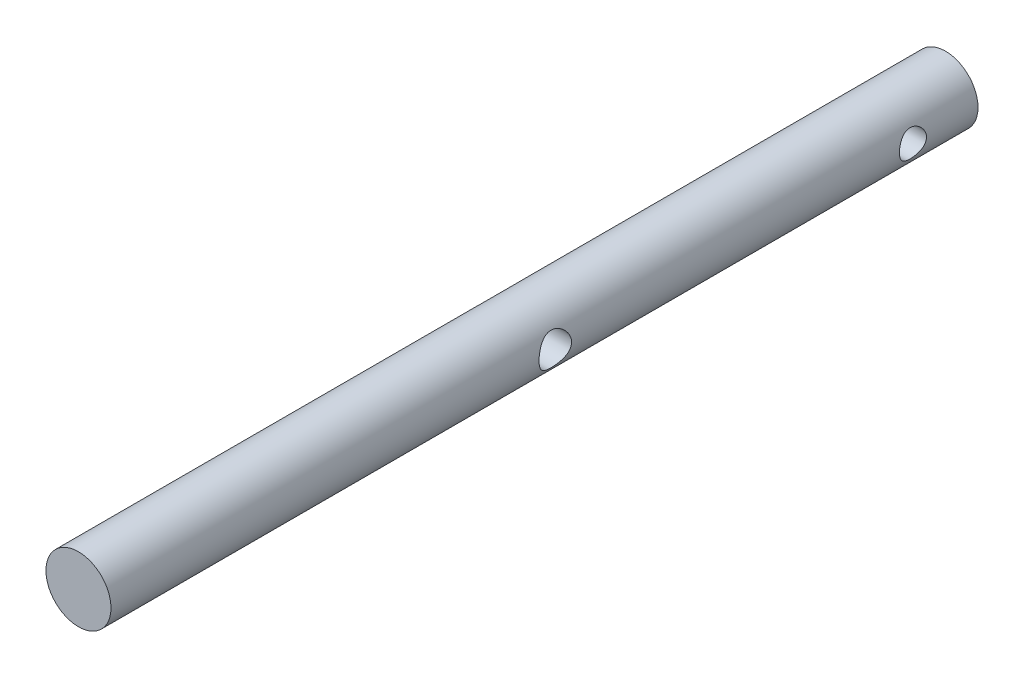
SolidWorks part; units mm, degrees
ref_plane "Front" through (0, 0, 0) normal (0, 0, 1) x (1, 0, 0)
ref_plane "Top" through (0, 0, 0) normal (0, 1, 0) x (1, 0, 0)
ref_plane "Right" through (0, 0, 0) normal (1, 0, 0) x (0, 0, -1)
sketch "Esquisse1" plane through (0, 0, 0) normal (0, 0, 1) x (1, 0, 0)
  circle A0 centre (0, 0) radius 2 construction
  circle A1 centre (0, 0) radius 3
  dimension "D1" = 6
  dimension "D2" = 4
extrude "Boss.-Extru.1" add sketch "Esquisse1" along normal blind 80
sketch "Esquisse2" plane through (0, 0, 0) normal (1, 0, 0) x (0, 0, -1)
  line L0 (0, -3) -> (0, 3) construction
  circle A0 centre (-6, 0) radius 1.25
  circle A1 centre (-39, 0) radius 1.5
  dimension "D1" = 2.5
  dimension "D2" = 6
  dimension "D3" = 3
  dimension "D4" = 33
extrude "Enlèv. mat.-Extru.1" cut sketch "Esquisse2" against normal through all both and the other way through all
sketch "Esquisse3" plane through (0, 0, 0) normal (1, 0, 0) x (0, 0, -1)
  circle A0 centre (-39, 0) radius 3
  dimension "D1" = 6
extrude "Enlèv. mat.-Extru.2" cut sketch "Esquisse3" against normal mid plane 2 from offset 3
